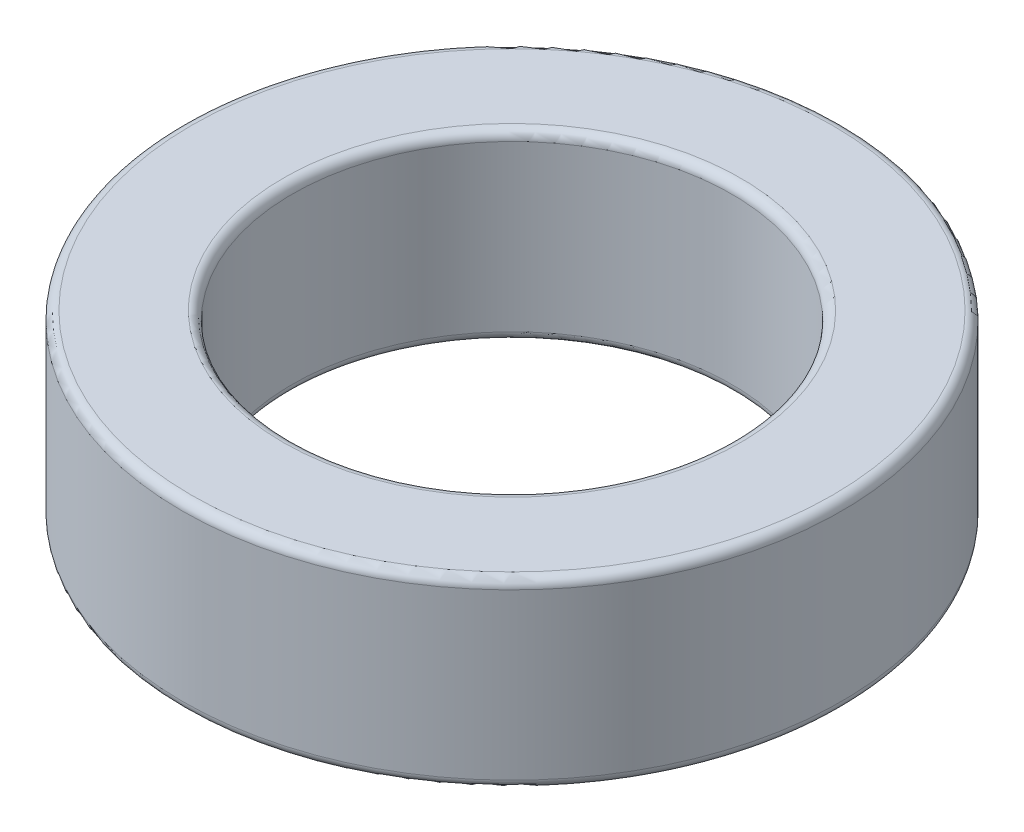
SolidWorks part; units mm, degrees
ref_plane "前视基准面" through (0, 0, 0) normal (0, 0, 1) x (1, 0, 0)
ref_plane "上视基准面" through (0, 0, 0) normal (0, 1, 0) x (1, 0, 0)
ref_plane "右视基准面" through (0, 0, 0) normal (1, 0, 0) x (0, 0, -1)
other "Configuration Table"
sketch "草图1" plane through (0, 0, 0) normal (0, 1, 0) x (1, 0, 0)
  circle A0 centre (0, 0) radius 9
  circle A1 centre (0, 0) radius 6
  dimension "D1" = 12
  dimension "D2" = 18
extrude "凸台-拉伸1" add sketch "草图1" along normal blind 5
fillet "圆角1" radius 0.25 4 edges at (0, 0, 6) (0, 5, 6) (0, 0, 9) (0, 5, 9)
